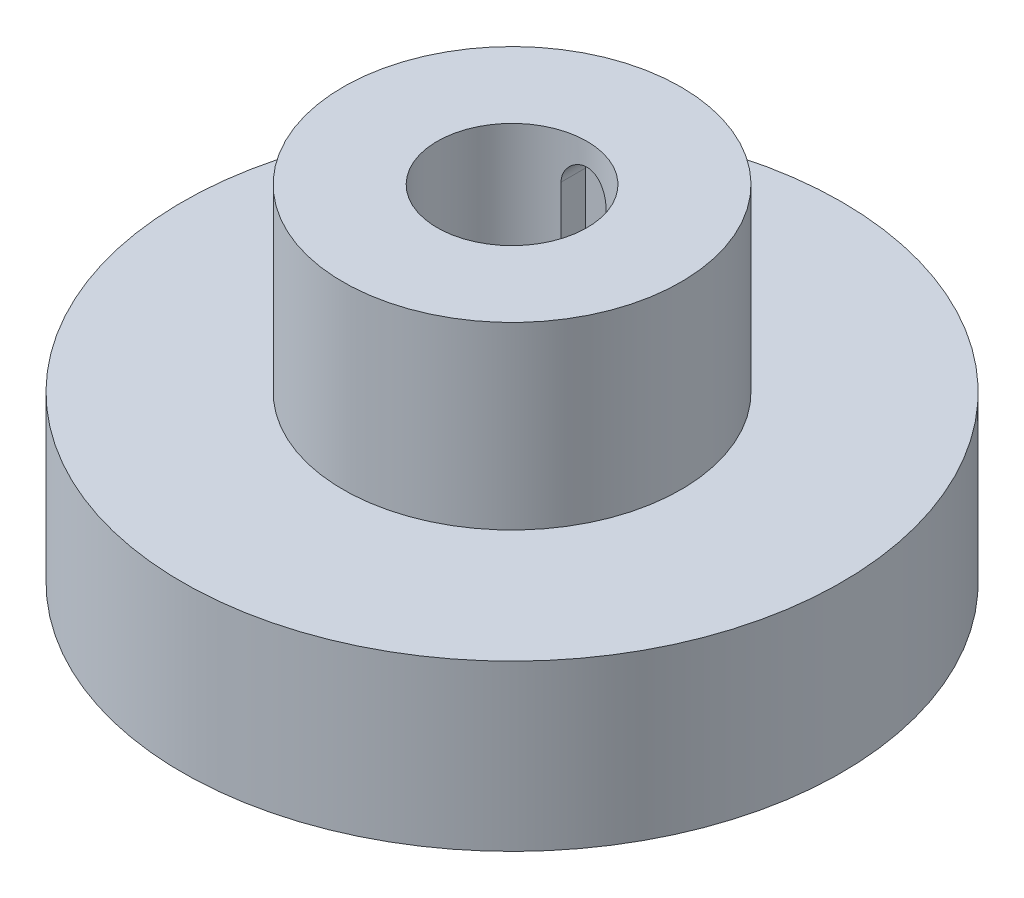
SolidWorks part; units mm, degrees
ref_plane "Front" through (0, 0, 0) normal (0, 0, 1) x (1, 0, 0)
ref_plane "Top" through (0, 0, 0) normal (0, 1, 0) x (1, 0, 0)
ref_plane "Right" through (0, 0, 0) normal (1, 0, 0) x (0, 0, -1)
sketch "Эскиз1" plane through (0, 0, 0) normal (0, 0, 1) x (1, 0, 0)
  line L0 (0, 0) -> (0, 6.9221) construction
  line L1 (5, 23) -> (5, 0)
  line L2 (5, 0) -> (22, 0)
  line L3 (22, 0) -> (22, 11)
  line L4 (22, 11) -> (11.2793, 11)
  line L5 (11.2793, 11) -> (11.2793, 23)
  line L6 (11.2793, 23) -> (5, 23)
  dimension "D1" = 44
  dimension "D2" = 10
  dimension "D3" = 23
  dimension "D4" = 12
revolve "Повернуть1" add sketch "Эскиз1" angle 360 about L0
sketch "Эскиз2" plane through (0, 0, 0) normal (0, 0, 1) x (1, 0, 0)
  line L0 (0, 5) -> (0, 20) construction
  line L1 (-1.5, 5) -> (-1.5, 20)
  line L2 (1.5, 5) -> (1.5, 20)
  arc A0 (-1.5, 5) -> (1.5, 5) centre (0, 5) ccw
  arc A1 (1.5, 20) -> (-1.5, 20) centre (0, 20) ccw
  point P3 (0, 12.5)
  dimension "D3" = 1.5
  dimension "D1" = 15
  dimension "D2" = 5
extrude "Вырез-Вытянуть1" cut sketch "Эскиз2" against normal blind 6.4 contours A1 L1 A0 L2
